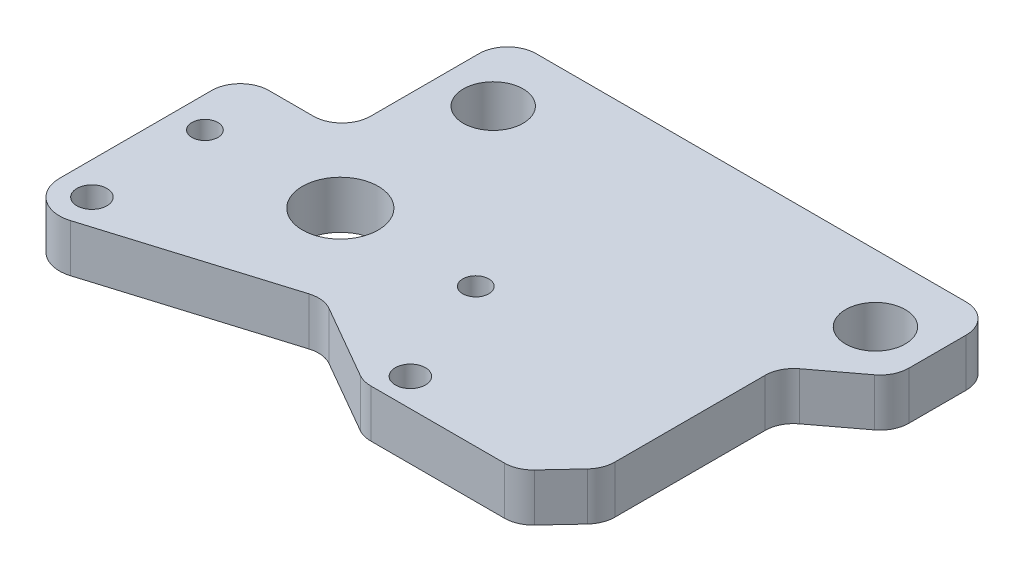
SolidWorks part; units mm, degrees
other "Markup1"
sketch "Sketch6" plane through (-23.3268, 0, -30.7975) normal (-0.0348, 0.9994, -0.0028) x (-0.9993, -0.0348, 0.0153)
sketch "Sketch7" plane through (-23.3268, 0, -30.7975) normal (-0.0348, 0.9994, -0.0028) x (-0.9993, -0.0348, 0.0153)
sketch "Sketch8" plane through (-23.3268, 0, -30.7975) normal (-0.0348, 0.9994, -0.0028) x (-0.9993, -0.0348, 0.0153)
sketch "Sketch10" plane through (-23.3268, 0, -30.7975) normal (-0.0348, 0.9994, -0.0028) x (-0.9993, -0.0348, 0.0153)
sketch "Sketch13" plane through (-23.3268, 0, -30.7975) normal (-0.0348, 0.9994, -0.0028) x (-0.9993, -0.0348, 0.0153)
sketch "Sketch15" plane through (-23.3268, 0, -30.7975) normal (-0.0348, 0.9994, -0.0028) x (-0.9993, -0.0348, 0.0153)
sketch "Sketch16" plane through (-23.3268, 0, -30.7975) normal (-0.0348, 0.9994, -0.0028) x (-0.9993, -0.0348, 0.0153)
sketch "Sketch17" plane through (-23.3268, 0, -30.7975) normal (-0.0348, 0.9994, -0.0028) x (-0.9993, -0.0348, 0.0153)
sketch "Sketch18" plane through (-23.3268, 0, -30.7975) normal (-0.0348, 0.9994, -0.0028) x (-0.9993, -0.0348, 0.0153)
sketch "Sketch19" plane through (-23.3268, 0, -30.7975) normal (-0.0348, 0.9994, -0.0028) x (-0.9993, -0.0348, 0.0153)
sketch "Sketch21" plane through (-23.3268, 0, -30.7975) normal (-0.0348, 0.9994, -0.0028) x (-0.9993, -0.0348, 0.0153)
sketch "Sketch23" plane through (-23.3268, 0, -30.7975) normal (-0.0348, 0.9994, -0.0028) x (-0.9993, -0.0348, 0.0153)
sketch "Sketch24" plane through (-23.3268, 0, -30.7975) normal (-0.0348, 0.9994, -0.0028) x (-0.9993, -0.0348, 0.0153)
sketch "Sketch25" plane through (-23.3268, 0, -30.7975) normal (-0.0348, 0.9994, -0.0028) x (-0.9993, -0.0348, 0.0153)
sketch "Sketch26" plane through (-23.3268, 0, -30.7975) normal (-0.0348, 0.9994, -0.0028) x (-0.9993, -0.0348, 0.0153)
sketch "Sketch27" plane through (-23.3268, 0, -30.7975) normal (-0.0348, 0.9994, -0.0028) x (-0.9993, -0.0348, 0.0153)
sketch "Sketch28" [suppressed] plane through (-23.3268, 0, -30.7975) normal (-0.0348, 0.9994, -0.0028) x (-0.9993, -0.0348, 0.0153)
sketch "Sketch29" plane through (-23.3268, 0, -30.7975) normal (-0.0348, 0.9994, -0.0028) x (-0.9993, -0.0348, 0.0153)
sketch "Sketch30" plane through (-23.3268, 0, -30.7975) normal (-0.0348, 0.9994, -0.0028) x (-0.9993, -0.0348, 0.0153)
sketch "Sketch32" plane through (-23.3268, 0, -30.7975) normal (-0.0348, 0.9994, -0.0028) x (-0.9993, -0.0348, 0.0153)
sketch "Sketch34" plane through (-23.3268, 0, -30.7975) normal (-0.0348, 0.9994, -0.0028) x (-0.9993, -0.0348, 0.0153)
sketch "Sketch35" plane through (-23.3268, 0, -30.7975) normal (-0.0348, 0.9994, -0.0028) x (-0.9993, -0.0348, 0.0153)
sketch "Sketch36" plane through (-23.3268, 0, -30.7975) normal (-0.0348, 0.9994, -0.0028) x (-0.9993, -0.0348, 0.0153)
sketch "Sketch37" plane through (-23.3268, 0, -30.7975) normal (-0.0348, 0.9994, -0.0028) x (-0.9993, -0.0348, 0.0153)
sketch "Sketch38" plane through (-23.3268, 0, -30.7975) normal (-0.0348, 0.9994, -0.0028) x (-0.9993, -0.0348, 0.0153)
sketch "Sketch39" plane through (-23.3268, 0, -30.7975) normal (-0.0348, 0.9994, -0.0028) x (-0.9993, -0.0348, 0.0153)
sketch "Sketch40" plane through (-23.3268, 0, -30.7975) normal (-0.0348, 0.9994, -0.0028) x (-0.9993, -0.0348, 0.0153)
sketch "Sketch41" [suppressed] plane through (-23.3268, 0, -30.7975) normal (-0.0348, 0.9994, -0.0028) x (-0.9993, -0.0348, 0.0153)
sketch "Sketch42" [suppressed] plane through (-23.3268, 0, -30.7975) normal (-0.0348, 0.9994, -0.0028) x (-0.9993, -0.0348, 0.0153)
sketch "Sketch43" plane through (-23.3268, 0, -30.7975) normal (-0.0348, 0.9994, -0.0028) x (-0.9993, -0.0348, 0.0153)
sketch "Sketch44" plane through (-23.3268, 0, -30.7975) normal (-0.0348, 0.9994, -0.0028) x (-0.9993, -0.0348, 0.0153)
sketch "Sketch45" plane through (-23.3268, 0, -30.7975) normal (-0.0348, 0.9994, -0.0028) x (-0.9993, -0.0348, 0.0153)
sketch "Sketch46" plane through (-23.3268, 0, -30.7975) normal (-0.0348, 0.9994, -0.0028) x (-0.9993, -0.0348, 0.0153)
sketch "Sketch47" plane through (-23.3268, 0, -30.7975) normal (-0.0348, 0.9994, -0.0028) x (-0.9993, -0.0348, 0.0153)
sketch "Sketch48" plane through (-23.3268, 0, -30.7975) normal (-0.0348, 0.9994, -0.0028) x (-0.9993, -0.0348, 0.0153)
sketch "Sketch49" [suppressed] plane through (-23.3268, 0, -30.7975) normal (-0.0348, 0.9994, -0.0028) x (-0.9993, -0.0348, 0.0153)
sketch "Sketch50" [suppressed] plane through (-23.3268, 0, -30.7975) normal (-0.0348, 0.9994, -0.0028) x (-0.9993, -0.0348, 0.0153)
sketch "Sketch51" plane through (-23.3268, 0, -30.7975) normal (-0.0348, 0.9994, -0.0028) x (-0.9993, -0.0348, 0.0153)
sketch "Sketch52" plane through (-23.3268, 0, -30.7975) normal (-0.0348, 0.9994, -0.0028) x (-0.9993, -0.0348, 0.0153)
material "6061-T6 (SS)"
ref_plane "X-Y Datum" through (0, 0, 0) normal (0, 0, 1) x (1, 0, 0)
ref_plane "X-Z Datum" through (0, 0, 0) normal (0, 1, 0) x (1, 0, 0)
ref_plane "Y-Z Datum" through (0, 0, 0) normal (1, 0, 0) x (0, 0, -1)
other "Graphic1"
other "Graphic (Closed) -1"
other "Graphic (Closed) -2"
sketch "Sketch2" plane through (0, 0, 0) normal (0, 1, 0) x (1, 0, 0)
  line L0 (48.6426, -18.7325) -> (-23.0162, -18.7325)
  line L1 (24.0125, -14.7036) -> (25.7865, -13.7801) construction
  line L2 (0, 0) -> (105.5557, -202.7707) construction
  line L3 (11.142, -21.4036) -> (-3.5026, -29.027) construction
  line L4 (0, 0) -> (0, -121.3797) construction
  line L5 (-3.5026, -29.027) -> (90.9112, -210.3941) construction
  line L6 (90.9112, -210.3941) -> (105.5557, -202.7707) construction
  line L7 (11.142, -21.4036) -> (24.0125, -14.7036) construction
  line L11 (-12.7, 30.7975) -> (57.15, 30.7975)
  line L12 (57.15, 13.0175) -> (57.15, 30.7975)
  line L13 (57.15, 13.0175) -> (-12.7, 13.0175) construction
  line L15 (44.7685, -18.0975) -> (44.7685, -11.3157) construction
  line L16 (44.7685, -18.0975) -> (34.8625, -18.0975) construction
  line L18 (44.7685, 9.8425) -> (34.8625, 9.8425) construction
  line L20 (44.7685, -11.3157) -> (49.8485, -11.3157) construction
  line L21 (49.8485, -11.3157) -> (49.8485, 3.0607) construction
  line L22 (49.8485, 3.0607) -> (44.7685, 3.0607) construction
  line L23 (44.7685, 3.0607) -> (44.7685, 9.8425) construction
  line L24 (34.8625, -18.0975) -> (34.8625, 9.8425) construction
  line L25 (48.6426, -18.7325) -> (57.15, 13.0175)
  line L26 (-12.7, 30.7975) -> (-12.7, 13.0175)
  line L28 (-12.5603, 0) -> (-16.51, -40.5272) construction
  line L30 (-23.0162, -18.7325) -> (-12.7, 13.0175)
  circle A0 centre (0, 0) radius 3.175
  circle A1 centre (24.0125, -14.7036) radius 2
  circle A2 centre (-1.5875, 21.9075) radius 3.9688
  circle A3 centre (49.2125, 21.9075) radius 3.9687
  circle A4 centre (39.8485, -4.1275) radius 5.1
  circle A5 centre (24.0125, -14.7036) radius 3.175 construction
  circle A6 centre (39.8485, -14.6275) radius 1.6
  circle A7 centre (39.8485, 6.3725) radius 1.6
  circle A8 centre (-17.2047, -14.9225) radius 3.175 construction
  circle A9 centre (-17.2047, -14.9225) radius 2
  point P9 (11.142, -21.4036)
  point P30 (49.8485, -4.1275)
  point P31 (34.8625, -4.1275)
  dimension "D1" = 6.35
  dimension "D8" = 4
  dimension "D10" = 7.9375
  dimension "D11" = 7.9375
  dimension "D16" = 27.94
  dimension "D23" = 10.2
  dimension "D20" = 6.35
  dimension "D30" = 3.2
  dimension "D32" = 3.2
  dimension "D34" = 6.35
  dimension "D35" = 4
  dimension "D3" = 13.0175
  dimension "D4" = 16.51
  dimension "D5" = 228.6
  dimension "D6" = 24.13
  dimension "D7" = 27.5
  dimension "D9" = 16.51
  dimension "D12" = 8.89
  dimension "D13" = 69.85
  dimension "D14" = 7.9375
  dimension "D15" = 31.75
  dimension "D17" = 17.78
  dimension "D18" = 3.175
  dimension "D19" = 14.986
  dimension "D21" = 5.08
  dimension "D22" = 14.3764
  dimension "D24" = 10
  dimension "D25" = 36.83
  dimension "D26" = 50.8
  dimension "D27" = 165
  dimension "D28" = 12.7
  dimension "D29" = 17.3015
  dimension "D31" = 10.5
  dimension "D33" = 10.5
  dimension "D36" = 162
extrude "Boss-Extrude1" [suppressed] add sketch "Sketch2" against normal blind 6.35
ref_point "Point1" [suppressed]
sketch "Sketch3" [suppressed] plane through (0, 0, 0) normal (0, 1, 0) x (1, 0, 0)
  line L0 (39.9681, 6.3725) -> (39.9681, -4.1275) construction
  line L1 (57.2697, 12.9663) -> (-12.5803, 12.9663) construction
  line L5 (39.9681, -4.1275) -> (39.9681, -14.6275) construction
  line L6 (42.0297, -18.7325) -> (20.4164, -18.7325)
  line L7 (57.2697, 12.9663) -> (57.2697, 30.7975)
  line L8 (57.2697, 30.7975) -> (-12.5803, 30.7975)
  line L9 (-12.5803, 30.7975) -> (-12.5803, 12.9663)
  line L10 (40.938, 24.6176) -> (16.9472, 10.7666)
  line L11 (13.3942, 11.8528) -> (6.9035, 25.1608)
  line L12 (8.045, 26.9875) -> (40.303, 26.9875)
  line L13 (57.2697, 12.9663) -> (48.3797, 12.9663)
  line L14 (48.3797, 12.9663) -> (48.3797, -12.3825)
  line L16 (-23.0162, -18.7325) -> (48.6426, -18.7325) construction
  line L18 (16.6064, -14.8627) -> (10.2787, -14.8627)
  line L21 (-8.965, -15.5427) -> (-15.106, -18.7325)
  line L24 (-21.1701, -13.6017) -> (-12.5803, 12.9663)
  line L29 (17.8764, -16.1925) -> (17.8764, -16.1327)
  circle A0 centre (0.1197, 0) radius 3.175
  circle A1 centre (-1.4678, 21.9075) radius 3.9688
  circle A2 centre (49.3322, 21.9075) radius 3.9687
  circle A3 centre (39.9681, -4.1275) radius 5.1
  circle A4 centre (39.9681, -14.6275) radius 1.6
  circle A5 centre (39.9681, 6.3725) radius 1.6
  circle A6 centre (24.1322, -14.7036) radius 2
  circle A7 centre (-17.085, -14.9225) radius 2
  arc A8 (13.3942, 11.8528) -> (16.9472, 10.7666) centre (15.6772, 12.9663) ccw
  arc A9 (8.045, 26.9875) -> (6.9035, 25.1608) centre (8.045, 25.7175) ccw
  arc A10 (40.938, 24.6176) -> (40.303, 26.9875) centre (40.303, 25.7175) ccw
  arc A11 (10.2787, -14.8627) -> (-8.965, -15.5427) centre (0.1197, 0) cw
  arc A12 (-15.106, -18.7325) -> (-21.1701, -13.6017) centre (-17.085, -14.9225) cw
  arc A13 (42.0297, -18.7325) -> (48.3797, -12.3825) centre (42.0297, -12.3825) ccw
  arc A14 (20.4164, -18.7325) -> (17.8764, -16.1925) centre (20.4164, -16.1925) cw
  arc A15 (16.6064, -14.8627) -> (17.8764, -16.1327) centre (16.6064, -16.1327) cw
  dimension "D1" = 6.35
  dimension "D4" = 7.9375
  dimension "D9" = 10.2
  dimension "D10" = 3.2
  dimension "D11" = 4
  dimension "D21" = 2.54
  dimension "D22" = 1.27
  dimension "D3" = 6.35
  dimension "D28" = 2.54
  dimension "D29" = 1.27
  dimension "D2" = 7.9375
  dimension "D5" = 50.8
  dimension "D6" = 21.9075
  dimension "D7" = 1.5875
  dimension "D8" = 8.89
  dimension "D12" = 10.5
  dimension "D13" = 17.2047
  dimension "D14" = 24.0125
  dimension "D15" = 14.7036
  dimension "D16" = 39.8485
  dimension "D17" = 4.1275
  dimension "D18" = 14.9225
  dimension "D19" = 69.85
  dimension "D20" = 3.81
  dimension "D23" = 30
  dimension "D24" = 64
  dimension "D25" = 32.258
  dimension "D26" = 15.5575
  dimension "D27" = 25.3488
  dimension "D30" = 8.89
sketch "Sketch4" plane through (0, 0, 0) normal (0, 1, 0) x (1, 0, 0)
  line L0 (39.8485, 6.3725) -> (39.8485, -4.1275) construction
  line L1 (56.1975, 13.0175) -> (-8.5725, 13.0175) construction
  line L2 (39.8485, -4.1275) -> (39.8485, -14.6275) construction
  line L3 (40.2577, -18.4375) -> (22.4839, -18.4375)
  line L5 (52.3875, 30.7975) -> (-4.7625, 30.7975)
  line L6 (-8.5725, 26.9875) -> (-8.5725, 12.6075)
  line L40 (47.4685, 8.9851) -> (47.4685, -10.9806)
  line L41 (46.4449, -13.579) -> (43.0442, -17.2259)
  line L43 (48.9856, 12.0279) -> (54.6804, 16.3193)
  line L44 (56.1975, 19.3621) -> (56.1975, 26.9875)
  line L50 (-17.78, -15.24) -> (0, 0) construction
  line L58 (20.5837, -17.9298) -> (10.7795, -12.2883)
  line L59 (0, 0) -> (0, 5.6144) construction
  line L60 (7.7656, -11.947) -> (-16.5178, -19.3694)
  line L61 (-22.098, -15.24) -> (-22.098, 4.9875)
  line L62 (-18.288, 8.7975) -> (-12.3825, 8.7975)
  circle A0 centre (0, 0) radius 5.04
  circle A1 centre (-1.5875, 21.9075) radius 3.9688
  circle A2 centre (49.2125, 21.9075) radius 3.9687
  circle A6 centre (24.0125, -14.7036) radius 2
  circle A7 centre (-17.78, -15.24) radius 2
  arc A12 (-16.5178, -19.3694) -> (-22.098, -15.24) centre (-17.78, -15.24) cw
  arc A19 (-8.5725, 26.9875) -> (-4.7625, 30.7975) centre (-4.7625, 26.9875) cw
  arc A20 (52.3875, 30.7975) -> (56.1975, 26.9875) centre (52.3875, 26.9875) cw
  circle A33 centre (24.0125, -14.7036) radius 3.5 construction
  arc A45 (56.1975, 19.3621) -> (54.6804, 16.3193) centre (52.3875, 19.3621) cw
  arc A46 (47.4685, 8.9851) -> (48.9856, 12.0279) centre (51.2785, 8.9851) cw
  arc A47 (47.4685, -10.9806) -> (46.4449, -13.579) centre (43.6585, -10.9806) cw
  arc A48 (43.0442, -17.2259) -> (40.2577, -18.4375) centre (40.2577, -14.6275) cw
  arc A51 (-22.098, 4.9875) -> (-18.288, 8.7975) centre (-18.288, 4.9875) cw
  arc A52 (-12.3825, 8.7975) -> (-8.5725, 12.6075) centre (-12.3825, 12.6075) ccw
  arc A53 (22.4839, -18.4375) -> (20.5837, -17.9298) centre (22.4839, -14.6275) cw
  arc A54 (7.7656, -11.947) -> (10.7795, -12.2883) centre (8.8793, -15.5906) cw
  circle A55 centre (0, 0) radius 18 construction
  circle A57 centre (18, 0) radius 1.7272
  circle A58 centre (-18, 0) radius 1.7272
  point P30 (21.466, -18.4375)
  point P36 (9.3466, -11.4637)
  point P58 (-8.5725, 30.7975)
  point P77 (56.1975, 17.4625)
  point P84 (41.9143, -18.4375)
  dimension "D1" = 10.08
  dimension "D2" = 7.9375
  dimension "D7" = 22
  dimension "D8" = 4
  dimension "D19" = 3.81
  dimension "D20" = 6.9738
  dimension "D25" = 3.81
  dimension "D26" = 7
  dimension "D27" = 25.8644
  dimension "D31" = 3.4544
  dimension "D33" = 4.318
  dimension "D23" = 3.81
  dimension "D45" = 3.81
  dimension "D18" = 3.81
  dimension "D29" = 3.81
  dimension "D30" = 36
  dimension "D3" = 50.8
  dimension "D4" = 21.9075
  dimension "D5" = 1.5875
  dimension "D9" = 10.5
  dimension "D10" = 24.0125
  dimension "D11" = 14.7036
  dimension "D12" = 39.8485
  dimension "D13" = 4.1275
  dimension "D14" = 15.24
  dimension "D15" = 17.78
  dimension "D16" = 6.985
  dimension "D17" = 8.89
  dimension "D21" = 17.78
  dimension "D22" = 12.1194
  dimension "D24" = 7.62
  dimension "D28" = 4.9865
  dimension "D36" = 9.525
  dimension "D40" = 127
  dimension "D43" = 137
  dimension "D60" = 6.985
extrude "Boss-Extrude2" add sketch "Sketch4" against normal blind 6.35
ref_point "Point2"
ref_point "Point3"
ref_point "Point4"
